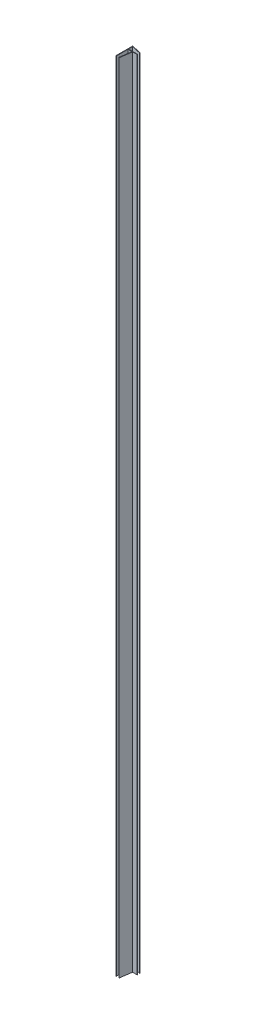
SolidWorks part; units mm, degrees
ref_plane "Front Plane" through (0, 0, 0) normal (0, 0, 1) x (1, 0, 0)
ref_plane "Top Plane" through (0, 0, 0) normal (0, 1, 0) x (1, 0, 0)
ref_plane "Right Plane" through (0, 0, 0) normal (1, 0, 0) x (0, 0, -1)
sketch "Sketch1" plane through (0, 0, 0) normal (0, 1, 0) x (1, 0, 0)
  line L0 (-13.2, 22.0196) -> (-13.2, -22)
  line L1 (-12, -22) -> (12, -22) construction
  line L2 (-12, -22) -> (-12, 22) construction
  line L3 (-12, 22) -> (12, 22) construction
  line L4 (12, -22) -> (12, 22) construction
  line L5 (-12, -22) -> (12, 22) construction
  line L6 (-12, 22) -> (12, -22) construction
  line L7 (-12, -22) -> (-12, 8.5257)
  line L8 (-12, 8.5257) -> (-1.2, 8.5257)
  line L9 (-1.2, 8.5257) -> (-5.5, -22)
  line L10 (-5.5, -22) -> (-4.2882, -22)
  line L11 (-4.2882, -22) -> (0.0118, 8.5257)
  line L12 (0.0118, 8.5257) -> (12, 8.5257)
  line L13 (12, 8.5257) -> (12, 9.7257)
  line L14 (12, 9.7257) -> (-12, 9.7257)
  line L15 (-12, 9.7257) -> (-12, 20.5257)
  line L16 (-12, 20.5257) -> (12, 15.2257)
  line L17 (12, 15.2257) -> (12, 16.4546)
  line L18 (12, 16.4546) -> (-13.2, 22.0196)
  line L19 (-12, -22) -> (-13.2, -22)
  point P0 (0, 0)
  dimension "D1" = 44
  dimension "D2" = 24
  dimension "D3" = 1.2
  dimension "D4" = 1.2
  dimension "D5" = 1.2
  dimension "D6" = 1.2
  dimension "D7" = 5.5
  dimension "D8" = 6.5
  dimension "D9" = 10.8
  dimension "D10" = 10.8
  dimension "D11" = 10.8
extrude "Boss-Extrude1" add sketch "Sketch1" along normal blind 2080.72
